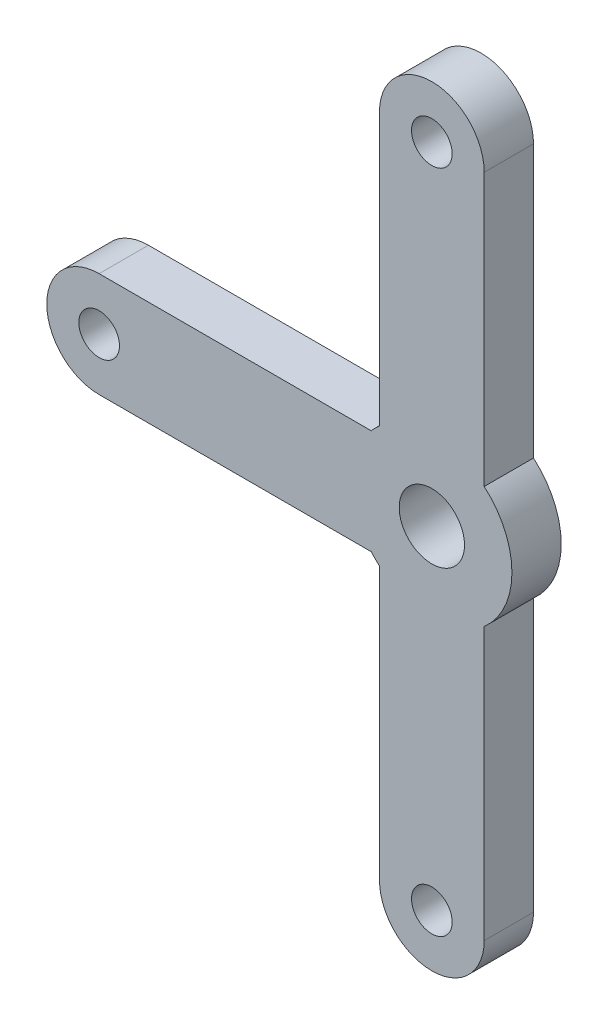
SolidWorks part; units mm, degrees
ref_plane "Front Plane" through (0, 0, 0) normal (0, 0, 1) x (1, 0, 0)
ref_plane "Top Plane" through (0, 0, 0) normal (0, 1, 0) x (1, 0, 0)
ref_plane "Right Plane" through (0, 0, 0) normal (1, 0, 0) x (0, 0, -1)
sketch "S01 - Central spindle pad" plane through (0, 0, 0) normal (0, 0, 1) x (1, 0, 0)
  circle A0 centre (0, 0) radius 13
  dimension "D1" = 26
extrude "01 - Central spindle pad" add sketch "S01 - Central spindle pad" along normal blind 8
sketch "S02 - Cage rib 1" plane through (0, 0, 0) normal (0, 0, 1) x (1, 0, 0)
  line L0 (-8.5, 0) -> (-8.5, 54)
  line L1 (8.5, 54) -> (8.5, 0)
  arc A0 (-8.5, 54) -> (8.5, 54) centre (0, 54) cw
  arc A1 (8.5, 0) -> (-8.5, 0) centre (0, 0) cw
  dimension "D1" = 8.5
  dimension "D2" = 54
extrude "02 - Cage rib 1" add sketch "S02 - Cage rib 1" along normal blind 8
sketch "S03 - Cage rib 2" plane through (0, 0, 0) normal (0, 0, 1) x (1, 0, 0)
  line L0 (0, -8.5) -> (-54, -8.5)
  line L1 (-54, 8.5) -> (0, 8.5)
  arc A0 (-54, -8.5) -> (-54, 8.5) centre (-54, 0) cw
  arc A1 (0, 8.5) -> (0, -8.5) centre (0, 0) cw
  dimension "D1" = 8.5
  dimension "D2" = 54
extrude "03 - Cage rib 2" add sketch "S03 - Cage rib 2" along normal blind 8
sketch "S04 - Cage rib 3" plane through (0, 0, 0) normal (0, 0, 1) x (1, 0, 0)
  line L0 (8.5, 0) -> (8.5, -54)
  line L1 (-8.5, -54) -> (-8.5, 0)
  arc A0 (8.5, -54) -> (-8.5, -54) centre (0, -54) cw
  arc A1 (-8.5, 0) -> (8.5, 0) centre (0, 0) cw
  dimension "D1" = 8.5
  dimension "D2" = 54
extrude "04 - Cage rib 3" add sketch "S04 - Cage rib 3" along normal blind 8
sketch "S05 - Three cage bolt holes" plane through (0, 0, 0) normal (0, 0, 1) x (1, 0, 0)
  circle A0 centre (0, 54) radius 3.3
  circle A1 centre (-54, 0) radius 3.3
  circle A2 centre (0, -54) radius 3.3
  dimension "D1" = 6.6
  dimension "D2" = 6.6
  dimension "D3" = 6.6
  dimension "D4" = 54
  dimension "D5" = 54
  dimension "D6" = 54
extrude "05 - Three cage bolt holes" cut sketch "S05 - Three cage bolt holes" along normal blind 10 from offset 1 offset against normal yes
sketch "S06 - Spindle stem clearance" plane through (0, 0, 0) normal (0, 0, 1) x (1, 0, 0)
  circle A0 centre (0, 0) radius 5.3
  dimension "D1" = 10.6
extrude "06 - Spindle stem clearance" cut sketch "S06 - Spindle stem clearance" along normal blind 10 from offset 1
